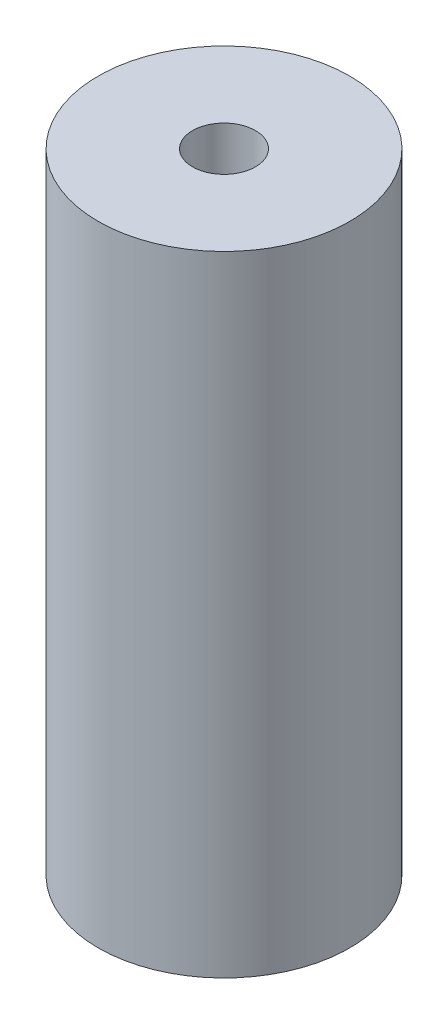
SolidWorks part; units mm, degrees
ref_plane "前视基准面" through (0, 0, 0) normal (0, 0, 1) x (1, 0, 0)
ref_plane "上视基准面" through (0, 0, 0) normal (0, 1, 0) x (1, 0, 0)
ref_plane "右视基准面" through (0, 0, 0) normal (1, 0, 0) x (0, 0, -1)
sketch "草图1" plane through (0, 0, 0) normal (0, 1, 0) x (1, 0, 0)
  circle A0 centre (0, 0) radius 40
  dimension "D1" = 80
extrude "凸台-拉伸1" add sketch "草图1" along normal blind 200
sketch "草图2" plane through (0, 200, 0) normal (0, 1, 0) x (1, 0, 0)
  circle A0 centre (0, 0) radius 10
  dimension "D1" = 20
extrude "切除-拉伸1" cut sketch "草图2" against normal through all
